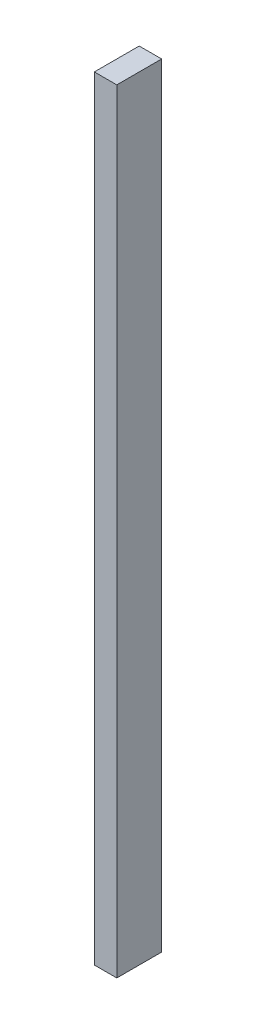
SolidWorks part; units mm, degrees
ref_plane "Front Plane" through (0, 0, 0) normal (0, 0, 1) x (1, 0, 0)
ref_plane "Top Plane" through (0, 0, 0) normal (0, 1, 0) x (1, 0, 0)
ref_plane "Right Plane" through (0, 0, 0) normal (1, 0, 0) x (0, 0, -1)
sketch "Sketch1" plane through (0, 0, 0) normal (0, 1, 0) x (1, 0, 0)
  line L1 (-12.7, -25.4) -> (12.7, -25.4)
  line L2 (-12.7, -25.4) -> (-12.7, 25.4)
  line L3 (-12.7, 25.4) -> (12.7, 25.4)
  line L4 (12.7, -25.4) -> (12.7, 25.4)
  line L5 (-12.7, -25.4) -> (12.7, 25.4) construction
  line L6 (-12.7, 25.4) -> (12.7, -25.4) construction
  point P0 (0, 0)
  dimension "D1" = 25.4
  dimension "D2" = 50.8
extrude "Boss-Extrude1" add sketch "Sketch1" along normal blind 875.792
